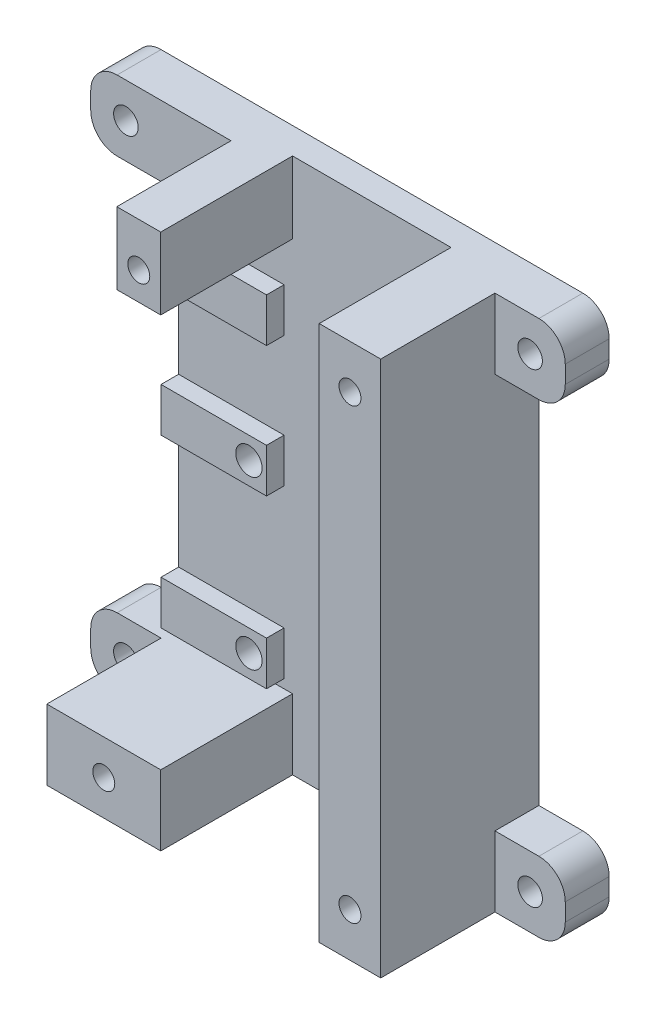
SolidWorks part; units mm, degrees
ref_plane "Plan de face" through (0, 0, 0) normal (0, 0, 1) x (1, 0, 0)
ref_plane "Plan de dessus" through (0, 0, 0) normal (0, 1, 0) x (1, 0, 0)
ref_plane "Plan de droite" through (0, 0, 0) normal (1, 0, 0) x (0, 0, -1)
sketch "Esquisse1" plane through (0, 0, 0) normal (0, 0, 1) x (1, 0, 0)
  line L1 (-17.5, -20) -> (17.5, -20)
  line L2 (-17.5, -20) -> (-17.5, 20)
  line L3 (-17.5, 20) -> (17.5, 20)
  line L4 (17.5, -20) -> (17.5, 20)
  line L5 (-17.5, -20) -> (17.5, 20) construction
  line L6 (-17.5, 20) -> (17.5, -20) construction
  point P0 (0, 0)
  dimension "D1" = 35
  dimension "D2" = 40
extrude "Boss.-Extru.1" add sketch "Esquisse1" along normal blind 3
sketch "Esquisse2" plane through (0, 0, 3) normal (0, 0, 1) x (1, 0, 0)
  line L0 (-17.5, 20) -> (-17.5, -20) construction
  line L1 (-7.5, 634.3767) -> (-7.0236, 615.3767) construction
  line L3 (-7.5, 2.5) -> (-7.5, -16.5) construction
  line L4 (-17.5, -20) -> (17.5, -20) construction
  circle A0 centre (-7.5, 634.3767) radius 2.0132
  circle A1 centre (-7.0236, 615.3767) radius 2.0132
  circle A2 centre (-7.5, 2.5) radius 1.5
  circle A3 centre (-7.5, -16.5) radius 1.5
  dimension "D3" = 3
  dimension "D1" = 19
  dimension "D2" = 10
  dimension "D4" = 10
  dimension "D5" = 19
  dimension "D6" = 22.5
extrude "Enlèv. mat.-Extru.1" cut sketch "Esquisse2" against normal blind 10
sketch "Esquisse3" plane through (0, -20, 0) normal (0, -1, 0) x (1, 0, 0)
  line L1 (-17.5, 3) -> (17.5, 3)
  line L2 (-17.5, 3) -> (-17.5, 0)
  line L3 (-17.5, 0) -> (17.5, 0)
  line L4 (17.5, 3) -> (17.5, 0)
extrude "Boss.-Extru.2" add sketch "Esquisse3" along normal blind 5
sketch "Esquisse4" plane through (0, 0, 3) normal (0, 0, 1) x (1, 0, 0)
  line L0 (17.5, -25) -> (-17.5, -25) construction
  line L1 (17.5, 20) -> (13.5, 20)
  line L2 (17.5, 20) -> (17.5, -25)
  line L3 (17.5, -25) -> (13.5, -25)
  line L4 (13.5, 20) -> (13.5, -25)
  line L6 (-17.5, -25) -> (-4.5339, -25)
  line L7 (-17.5, -25) -> (-17.5, -20)
  line L8 (-17.5, -20) -> (-4.5339, -20)
  line L9 (-4.5339, -25) -> (-4.5339, -20)
  dimension "D1" = 4
  dimension "D2" = 5
extrude "Boss.-Extru.3" add sketch "Esquisse4" along normal blind 15
sketch "Esquisse5" plane through (0, 20, 0) normal (0, 1, 0) x (1, 0, 0)
  line L6 (17.5, 0) -> (-17.5, 0)
  line L7 (-17.5, 0) -> (-17.5, -3)
  line L8 (-17.5, -3) -> (13.5, -3)
  line L9 (13.5, -3) -> (13.5, -18)
  line L10 (13.5, -18) -> (17.5, -18)
  line L11 (17.5, -18) -> (17.5, 0)
  line L12 (17.5, 0) -> (-17.5, 0)
  line L13 (-17.5, 0) -> (-17.5, -3)
  line L14 (-17.5, -3) -> (13.5, -3)
  line L15 (13.5, -3) -> (13.5, -18)
  line L16 (13.5, -18) -> (17.5, -18)
  line L17 (17.5, -18) -> (17.5, 0)
  dimension "D1" = 0
extrude "Boss.-Extru.4" add sketch "Esquisse5" along normal blind 10
sketch "Esquisse6" plane through (0, 0, 3) normal (0, 0, 1) x (1, 0, 0)
  line L0 (-17.5, 19.825) -> (13.5, 19.825) construction
  line L1 (-17.5, 30) -> (-17.5, -20) construction
  line L2 (-4.475, 19.825) -> (-20.575, 19.825) construction
  line L3 (13.5, 30) -> (13.5, -25) construction
  line L4 (-17.5, 30) -> (13.5, 30) construction
  line L5 (-4.5339, 30) -> (-9.5339, 30)
  line L6 (-4.5339, 30) -> (-4.5339, 24.825)
  line L7 (-4.5339, 24.825) -> (-9.5339, 24.825)
  line L8 (-9.5339, 30) -> (-9.5339, 24.825)
  line L9 (-4.5339, -20) -> (-4.5339, 30) construction
  dimension "D1" = 5
  dimension "D2" = 5
extrude "Boss.-Extru.5" add sketch "Esquisse6" along normal up to surface (15 mm away) up to face at (15.5, 2.5, 18)
sketch "Esquisse7" plane through (17.5, 0, 0) normal (1, 0, 0) x (0, 0, -1)
  line L4 (0, -25) -> (0, 30)
  line L5 (0, 30) -> (-18, 30)
  line L6 (-18, 30) -> (-18, -25)
  line L7 (-18, -25) -> (0, -25)
  line L8 (0, -25) -> (0, 30)
  line L9 (0, 30) -> (-18, 30)
  line L10 (-18, 30) -> (-18, -25)
  line L11 (-18, -25) -> (0, -25)
  dimension "D1" = 0
extrude "Boss.-Extru.6" add sketch "Esquisse7" along normal blind 3
sketch "Esquisse8" plane through (0, -25, 0) normal (0, -1, 0) x (1, 0, 0)
  line L8 (-17.5, 18) -> (-17.5, 0)
  line L9 (-17.5, 0) -> (20.5, 0)
  line L10 (20.5, 0) -> (20.5, 18)
  line L11 (20.5, 18) -> (13.5, 18)
  line L12 (13.5, 18) -> (13.5, 3)
  line L13 (13.5, 3) -> (-4.5339, 3)
  line L14 (-4.5339, 3) -> (-4.5339, 18)
  line L15 (-4.5339, 18) -> (-17.5, 18)
  line L16 (-17.5, 18) -> (-17.5, 0)
  line L17 (-17.5, 0) -> (20.5, 0)
  line L18 (20.5, 0) -> (20.5, 18)
  line L19 (20.5, 18) -> (13.5, 18)
  line L20 (13.5, 18) -> (13.5, 3)
  line L21 (13.5, 3) -> (-4.5339, 3)
  line L22 (-4.5339, 3) -> (-4.5339, 18)
  line L23 (-4.5339, 18) -> (-17.5, 18)
  dimension "D1" = 0
extrude "Boss.-Extru.7" add sketch "Esquisse8" along normal blind 3
sketch "Esquisse9" plane through (0, 30, 0) normal (0, 1, 0) x (1, 0, 0)
  line L10 (13.5, -18) -> (20.5, -18)
  line L11 (20.5, -18) -> (20.5, 0)
  line L12 (20.5, 0) -> (-17.5, 0)
  line L13 (-17.5, 0) -> (-17.5, -3)
  line L14 (-17.5, -3) -> (-9.5339, -3)
  line L15 (-9.5339, -3) -> (-9.5339, -18)
  line L16 (-9.5339, -18) -> (-4.5339, -18)
  line L17 (-4.5339, -18) -> (-4.5339, -3)
  line L18 (-4.5339, -3) -> (13.5, -3)
  line L19 (13.5, -3) -> (13.5, -18)
  line L20 (13.5, -18) -> (20.5, -18)
  line L21 (20.5, -18) -> (20.5, 0)
  line L22 (20.5, 0) -> (-17.5, 0)
  line L23 (-17.5, 0) -> (-17.5, -3)
  line L24 (-17.5, -3) -> (-9.5339, -3)
  line L25 (-9.5339, -3) -> (-9.5339, -18)
  line L26 (-9.5339, -18) -> (-4.5339, -18)
  line L27 (-4.5339, -18) -> (-4.5339, -3)
  line L28 (-4.5339, -3) -> (13.5, -3)
  line L29 (13.5, -3) -> (13.5, -18)
  dimension "D1" = 0
extrude "Boss.-Extru.8" add sketch "Esquisse9" along normal blind 3
sketch "Esquisse10" plane through (0, 0, 18) normal (0, 0, 1) x (1, 0, 0)
  line L0 (13.5, 33) -> (20.5, 33) construction
  line L1 (20.5, -28) -> (13.5, -28) construction
  line L2 (-7.0339, 24.825) -> (-7.0339, 33) construction
  line L3 (-4.5339, -24) -> (-17.5, -24) construction
  line L4 (-4.5339, -28) -> (-4.5339, -20) construction
  line L5 (-17.5, -20) -> (-17.5, -28) construction
  line L6 (17, 33) -> (17, -28) construction
  line L7 (17, 28) -> (-7.0339, 28) construction
  line L8 (-4.5339, 24.825) -> (-9.5339, 24.825) construction
  line L9 (-9.5339, 33) -> (-4.5339, 33) construction
  circle A0 centre (17, -23) radius 1.25
  circle A1 centre (17, 28) radius 1.25
  circle A2 centre (-11.0169, -24) radius 1.25
  circle A3 centre (-7.0339, 28) radius 1.25
  dimension "D3" = 2.5
  dimension "D1" = 5
  dimension "D2" = 5
extrude "Enlèv. mat.-Extru.2" cut sketch "Esquisse10" against normal blind 6
sketch "Esquisse11" plane through (20.5, 0, 0) normal (1, 0, 0) x (0, 0, -1)
  line L0 (0, 2.5) -> (-18, 2.5) construction
  line L1 (0, -28) -> (-5, -28)
  line L2 (0, -28) -> (0, -20)
  line L3 (0, -20) -> (-5, -20)
  line L4 (-5, -28) -> (-5, -20)
  line L5 (-18, 33) -> (-18, -28) construction
  line L6 (-5, 33) -> (-5, 25)
  line L7 (0, 25) -> (-5, 25)
  line L8 (0, 33) -> (0, 25)
  line L9 (0, 33) -> (-5, 33)
  line L10 (0, -28) -> (0, 33) construction
  line L11 (-18, -28) -> (-18, 33) construction
  dimension "D1" = 8
  dimension "D2" = 5
extrude "Boss.-Extru.9" add sketch "Esquisse11" along normal blind 8
ref_plane "Plan1" through (1.5, 0, 0) normal (1, 0, 0) x (0, 0, -1)
sketch "Esquisse12" plane through (0, 0, 5) normal (0, 0, 1) x (1, 0, 0)
  line L0 (24.5, -28) -> (24.5, 33) construction
  line L1 (28.5, -28) -> (20.5, -28) construction
  line L2 (28.5, 33) -> (20.5, 33) construction
  line L3 (28.5, -24) -> (20.5, -24) construction
  line L4 (28.5, -20) -> (28.5, -28) construction
  line L5 (20.5, -20) -> (20.5, -28) construction
  line L6 (28.5, -20) -> (28.5, 25) construction
  line L7 (24.5, 2.5) -> (28.5, 2.5) construction
  circle A0 centre (24.5, -24) radius 1.4
  circle A1 centre (24.5, 29) radius 1.4
  point P14 (24.5, -24)
  point P15 (24.5, -24)
  point P20 (28.5, 2.5)
  point P21 (24.5, 2.5)
  dimension "D1" = 2.8
extrude "Enlèv. mat.-Extru.3" cut sketch "Esquisse12" against normal blind 8
mirror "Symétrie1" about plane through (1.5, 0, 0) normal (1, 0, 0) of "Boss.-Extru.9", "Enlèv. mat.-Extru.3"
sketch "Esquisse13" plane through (0, 0, 3) normal (0, 0, 1) x (1, 0, 0)
  line L1 (-17.5, 33) -> (-9.5339, 33)
  line L2 (-17.5, 33) -> (-17.5, 24.825)
  line L3 (-17.5, 24.825) -> (-9.5339, 24.825)
  line L4 (-9.5339, 33) -> (-9.5339, 24.825)
extrude "Boss.-Extru.10" add sketch "Esquisse13" along normal up to surface (2 mm away) up to face at (-20.1, 29, 5)
sketch "Esquisse14" plane through (0, 0, 3) normal (0, 0, 1) x (1, 0, 0)
  line L0 (-17.5, 24.825) -> (-17.5, -20) construction
  line L1 (-5.5, 19.825) -> (-17.5, 19.825)
  line L2 (-5.5, 19.825) -> (-5.5, 14.825)
  line L3 (-5.5, 14.825) -> (-17.5, 14.825)
  line L4 (-17.5, 19.825) -> (-17.5, 14.825)
  line L5 (-7.175, 17.325) -> (-17.5, 17.325) construction
  line L6 (-5.5, 5) -> (-17.5, 5)
  line L7 (-5.5, 5) -> (-5.5, 0)
  line L8 (-5.5, 0) -> (-17.5, 0)
  line L9 (-17.5, 5) -> (-17.5, 0)
  line L10 (-5.5, -14) -> (-17.5, -14)
  line L11 (-5.5, -14) -> (-5.5, -19)
  line L12 (-5.5, -19) -> (-17.5, -19)
  line L13 (-17.5, -14) -> (-17.5, -19)
  line L14 (-7.5, 2.5) -> (-17.5, 2.5) construction
  line L15 (-7.5, -16.5) -> (-17.5, -16.5) construction
  circle A0 centre (-7.5, 2.5) radius 1.5
  circle A1 centre (-7.5, -16.5) radius 1.5
  circle A2 centre (-7.5, -16.5) radius 1.5 construction
  circle A3 centre (-7.5, 2.5) radius 1.5 construction
  dimension "D1" = 5
  dimension "D2" = 12
extrude "Boss.-Extru.12" add sketch "Esquisse14" along normal blind 2
fillet "Congé1" radius 3 8 edges at (-25.5, 33, 2.5) (-25.5, 25, 2.5) (-25.5, -28, 2.5) (-25.5, -20, 2.5) (28.5, 33, 2.5) (28.5, 25, 2.5) (28.5, -20, 2.5) (28.5, -28, 2.5)
sketch "Esquisse15" plane through (0, 0, 0) normal (0, 0, -1) x (-1, 0, 0)
  circle A0 centre (7.5, 2.5) radius 3.5
  circle A1 centre (7.5, -16.5) radius 3.5
  circle A2 centre (7.5, 2.5) radius 1.5
  circle A3 centre (7.5, -16.5) radius 1.5
  circle A4 centre (7.5, 2.5) radius 1.5 construction
  circle A5 centre (7.5, -16.5) radius 1.5 construction
  dimension "D1" = 7
extrude "Enlèv. mat.-Extru.4" cut sketch "Esquisse15" against normal blind 2
